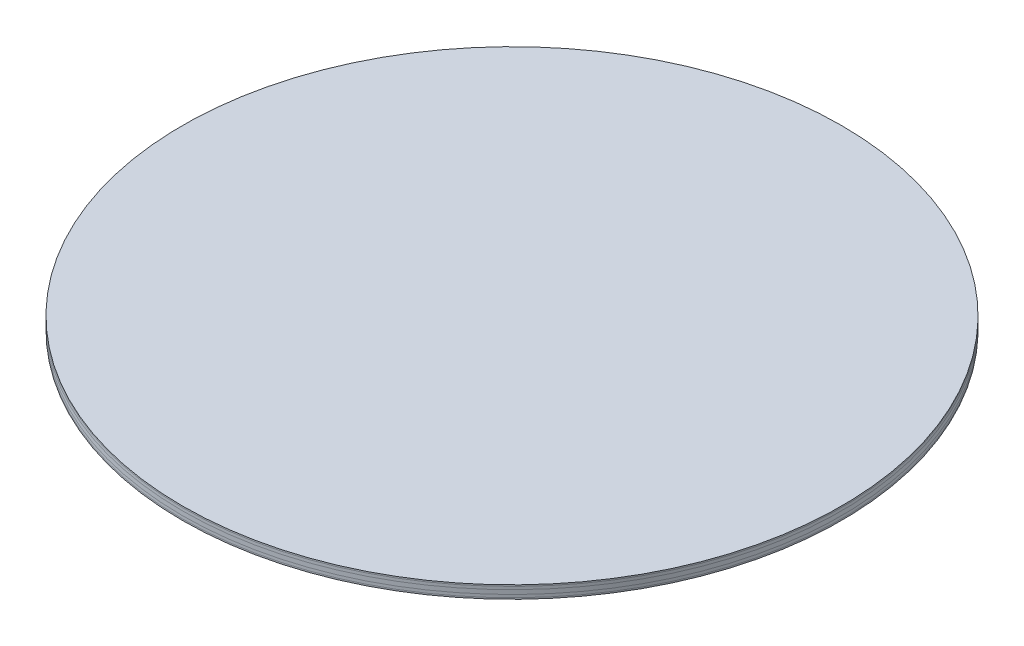
SolidWorks part; units mm, degrees
material "Beech"
ref_plane "Front Plane" through (0, 0, 0) normal (0, 0, 1) x (1, 0, 0)
ref_plane "Top Plane" through (0, 0, 0) normal (0, 1, 0) x (1, 0, 0)
ref_plane "Right Plane" through (0, 0, 0) normal (1, 0, 0) x (0, 0, -1)
sketch "Sketch1" plane through (0, 0, 0) normal (0, 1, 0) x (1, 0, 0)
  line L0 (-609.6, 609.6) -> (609.6, 609.6) construction
  line L1 (609.6, 609.6) -> (609.6, -609.6) construction
  line L2 (0, 609.6) -> (0, 0) construction
  line L3 (0, 0) -> (609.6, 0) construction
  dimension "Width" = 1219.2
  dimension "Length" = 1219.2
sketch "Sketch2" plane through (0, 0, 0) normal (1, 0, 0) x (0, 0, -1)
  line L0 (609.6, 0) -> (609.6, -19.05) construction
  dimension "Thickness" = 19.05
sketch "Sketch3" plane through (0, 0, 0) normal (0, 1, 0) x (1, 0, 0)
  line L1 (-609.6, 609.6) -> (609.6, 609.6)
  line L2 (-609.6, 609.6) -> (-609.6, -609.6)
  line L3 (-609.6, -609.6) -> (609.6, -609.6)
  line L4 (609.6, 609.6) -> (609.6, -609.6)
extrude "Boss-Extrude1" add sketch "Sketch3" against normal up to vertex (19.05 mm away) up to point (0, -19.05, -609.6)
sketch "Sketch4" plane through (0, 0, 0) normal (0, 0, 1) x (1, 0, 0)
  line L0 (0, -8.4667) -> (0, -10.5833) construction
  line L1 (-670.56, -16.9333) -> (670.56, -16.9333)
  line L2 (0, 0) -> (0, -19.05) construction
  line L3 (0, -8.4667) -> (0, -6.35) construction
  line L4 (0, -10.5833) -> (0, -12.7) construction
  line L5 (0, -6.35) -> (0, -4.2333) construction
  line L6 (0, -4.2333) -> (0, -2.1167) construction
  line L7 (0, -2.1167) -> (0, 0) construction
  line L8 (0, -12.7) -> (0, -14.8167) construction
  line L9 (0, -14.8167) -> (0, -16.9333) construction
  line L10 (0, -16.9333) -> (0, -19.05) construction
  line L11 (-670.56, -12.7) -> (670.56, -12.7)
  line L12 (-670.56, -2.1167) -> (670.56, -2.1167)
  line L13 (-670.56, -6.35) -> (670.56, -6.35)
  point P5 (0, -9.525)
  point P16 (0, -16.9333)
  point P19 (0, -12.7)
  point P23 (0, -2.1167)
  point P25 (0, -6.35)
  dimension "D1" = 1341.12
split "Split1" trim tools "Sketch4" bodies to split 104 resulting bodies 105 106 107 108 109
sketch "Sketch6" plane through (0, 0, 0) normal (0, 1, 0) x (1, 0, 0)
  circle A0 centre (0, 0) radius 500
  line M1 (-609.6, 609.6) -> (-609.6, -609.6)
  line M2 (-609.6, -609.6) -> (609.6, -609.6)
  line M3 (609.6, -609.6) -> (609.6, 609.6)
  line M4 (609.6, 609.6) -> (-609.6, 609.6)
extrude "Cut-Extrude1" cut sketch "Sketch6" against normal through all contours A0 M4 M1 M2 M3
equation "\"D1@Sketch4\"=\"Width@Sketch1\"*1.1"
